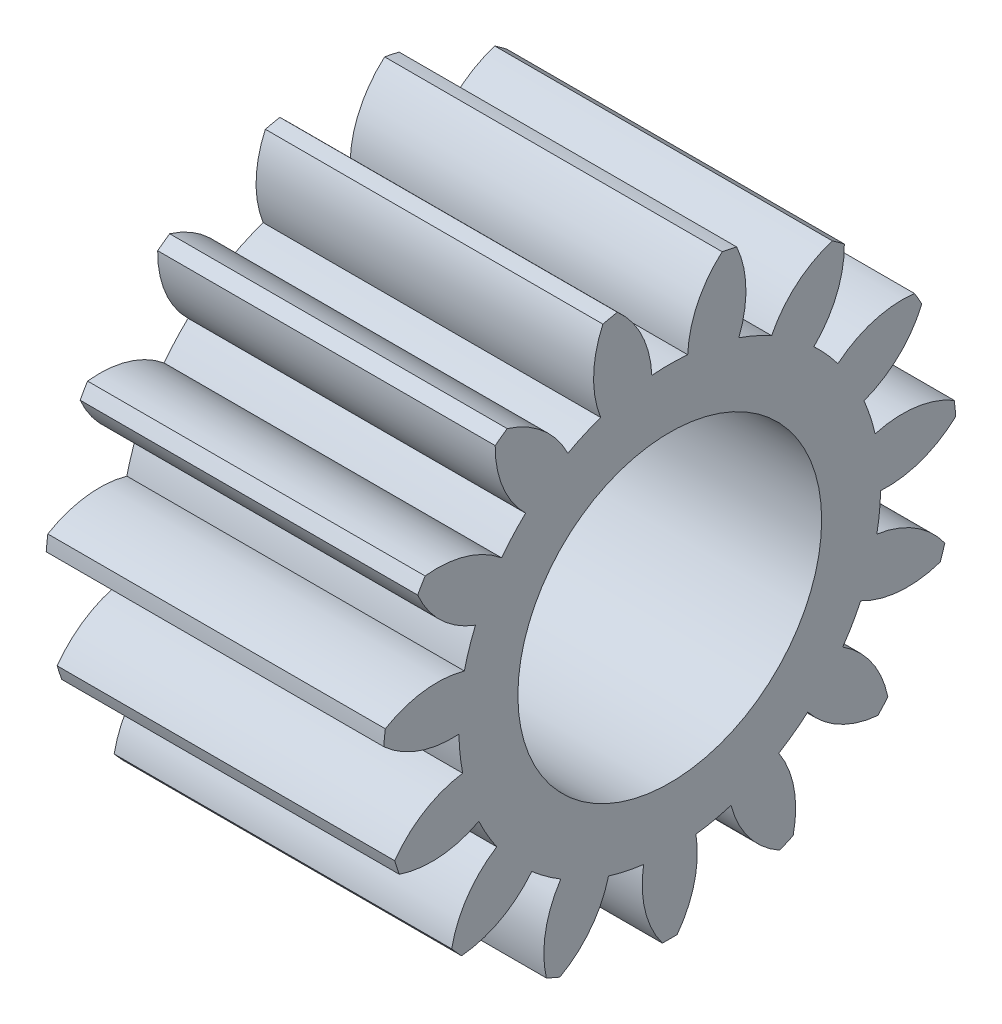
SolidWorks part; units mm, degrees
ref_plane "Plane1" through (0, 0, 0) normal (0, 0, 1) x (1, 0, 0)
ref_plane "Plane2" through (0, 0, 0) normal (0, 1, 0) x (1, 0, 0)
ref_plane "Plane3" through (0, 0, 0) normal (1, 0, 0) x (0, 0, -1)
other "Configuration Table"
sketch "HoldingSke" plane through (0, 0, 0) normal (0, 1, 0) x (1, 0, 0)
  line L0 (0, 0) -> (1.9319, -0.5176)
  line L1 (-15, 0) -> (100, 0) construction
  line L2 (0, 0) -> (-2.1039, 2.3779)
  line L3 (0, 0) -> (-11.863, 4.5341)
  line L4 (0, 0) -> (8.3417, 2.2352)
  line L5 (0, 0) -> (-46.8476, -17.4728)
  line L6 (0, 0) -> (-4.1448, -2.7965)
  line L7 (-2.1039, 2.3779) -> (8.6586, 51.2061)
  line L8 (-76.2, 54.61) -> (-75.7, 54.61)
  line L9 (-71.009, 38.7566) -> (-53.1078, 45.2721)
  line L10 (-76.2, 71.12) -> (104.1128, 71.12)
  line L11 (0, 0) -> (-5, 0)
  line L12 (-76.2, 101.6) -> (-76.181, 101.6)
  line L13 (24.9733, 27.94) -> (52.9518, 28.4284)
  line L14 (24.9733, 27.94) -> (24.9743, 27.94)
  line L15 (24.9733, 27.94) -> (100.4006, 29.5858)
  line L16 (-63.627, -0.5) -> (-12.827, -0.5)
  circle A0 centre (0, 0) radius 1.5
  circle A1 centre (0, 0) radius 3.124
  circle A2 centre (0, 0) radius 37.5
  circle A3 centre (0, 0) radius 2.25
  dimension "MHD" = 6.248
  dimension "Hub_dia" = 75
  dimension "Bore" = 3
  dimension "MBD" = 4.5
  dimension "Num_teeth" = 15
  dimension "Pitch" = 2
  dimension "Overall_len" = 50
  dimension "Show_teeth" = 15
  dimension "Thickness" = 5
  dimension "OAL" = 50.0003
  dimension "T_dim" = 0.5
  dimension "Ap" = 20
  dimension "H" = 19.05
  dimension "Pitch_radius" = 180.3128
  dimension "Width" = 5
  dimension "Backlash" = 0.019
  dimension "Addendum_fac" = 1
  dimension "Dedendum_fac" = 1.25
  dimension "Clearance_fac" = 0.25
  dimension "Dedendum_add" = 0.001
  dimension "Module" = 0.5
sketch "BasProSke" plane through (0, 0, 0) normal (0, 1, 0) x (1, 0, 0)
  line L0 (-10, 0) -> (60, 0) construction
  line L1 (0, 0) -> (0, 4.25)
  line L2 (0, 0) -> (5, 0)
  line L3 (5, 0) -> (5, 4.25)
  line L4 (5, 4.25) -> (0, 4.25)
  dimension "Thickness" = 5
  dimension "Diameter" = 8.5
revolve "Base-Revolve" add sketch "BasProSke" angle 360 about L0
sketch "TooCutSke" plane through (0, 0, 0) normal (1, 0, 0) x (0, 0, -1)
  line L1 (0, 0) -> (0, 107) construction
  line L2 (0, 0) -> (-0.4252, 3.7258) construction
  line L3 (0, 0) -> (-1.5522, 7.3025) construction
  line L4 (-0.4252, 3.7258) -> (-0.7761, 3.6512) construction
  arc A0 (0.2658, 3.1127) -> (-0.2658, 3.1127) centre (0, 0) ccw
  arc A1 (0.8008, 4.1997) -> (-0.8008, 4.1997) centre (0, 0) ccw
  circle A2 centre (0, 0) radius 3.75 construction
  circle A3 centre (0, 0) radius 3.5238 construction
  arc A4 (-0.2658, 3.1127) -> (-0.8008, 4.1997) centre (-1.7645, 3.0503) ccw
  arc A5 (0.8008, 4.1997) -> (0.2658, 3.1127) centre (1.7645, 3.0503) ccw
  dimension "Root_dia" = 6.248
  dimension "Overcut_dia" = 8.5508
  dimension "Pitch_dia" = 7.5
  dimension "Base_dia" = 7.0477
  dimension "Flank_rad" = 1.5
  dimension "Half_ang" = 12
  dimension "Half_CT" = 0.3587
extrude "ToothCut" cut sketch "TooCutSke" along normal through all
fillet "Breaks" [suppressed] radius 0.01
fillet "RootFillets" [suppressed] radius 0.126
pattern_circular "TeethCuts" count 15 every 24 about axis through (-10, 0, 0) along (1, 0, 0) of "ToothCut", "RootFillets", "Breaks"
sketch "HubNeaOneSke" plane through (0, 0, 0) normal (-1, 0, 0) x (0, 0, 1)
  circle A0 centre (0, 0) radius 3.124
  dimension "Diameter" = 6.248
extrude "HubNearOne" [suppressed] add sketch "HubNeaOneSke" along normal blind 45.0003
sketch "HubNeaBotSke" plane through (0, 0, 0) normal (-1, 0, 0) x (0, 0, 1)
  circle A0 centre (0, 0) radius 3.124
  dimension "Diameter" = 6.248
extrude "HubNearBoth" [suppressed] add sketch "HubNeaBotSke" along normal blind 22.5002
ref_plane "FarPln" through (5, 0, 0) normal (1, 0, 0) x (0, 0, -1)
sketch "HubFarSke" plane through (5, 0, 0) normal (1, 0, 0) x (0, 0, -1)
  circle A0 centre (0, 0) radius 3.124
  dimension "Diameter" = 6.248
extrude "HubFar" [suppressed] add sketch "HubFarSke" along normal blind 22.5002
sketch "BorSke" plane through (0, 0, 0) normal (1, 0, 0) x (0, 0, -1)
  circle A0 centre (0, 0) radius 2.25
  dimension "Diameter" = 4.5
extrude "Bore" cut sketch "BorSke" along normal mid plane 100.0006
sketch "KeySke" plane through (0, 0, 0) normal (1, 0, 0) x (0, 0, -1)
  line L0 (-0.6, 0) -> (-0.6, 2.75)
  line L1 (-0.6, 2.75) -> (0.6, 2.75)
  line L2 (0.6, 2.75) -> (0.6, 0)
  line L3 (0, 0) -> (0, 34) construction
  line L4 (-0.6, 0) -> (0.6, 0)
  dimension "Offset" = 2.75
  dimension "Width" = 1.2
extrude "Keyway" [suppressed] cut sketch "KeySke" along normal mid plane 100.0006
pattern_circular "Keyway2" [suppressed] count 2 every 90 about axis through (-10, 0, 0) along (1, 0, 0)
equation "' \"Module@HoldingSke\" = 6.35"
equation "' \"Num_teeth@HoldingSke\" = 12"
equation "' \"Ap@HoldingSke\" =  20"
equation "' \"Ap@HoldingSke\" = 20"
equation "' \"Width@HoldingSke\" = 0.5 * 25.4"
equation "' \"Hub_dia@HoldingSke\"= 1 * 25.4"
equation "' \"Hub_dia@HoldingSke\" = 1 * 25.4"
equation "' \"Overall_len@HoldingSke\" = 1.0 * 25.4"
equation "' \"Bore@HoldingSke\" = 0.75 * 25.4"
equation "' \"T_dim@HoldingSke\" = 0.1 * 25.4"
equation "' \"Width@KeySke\" = 0.25 * 25.4"
equation "' \"Show_teeth@HoldingSke\" = 13"
equation "' \"Backlash@HoldingSke\" = 0.009 * 25.4"
equation "' \"Addendum_fac@HoldingSke\" = 1.0"
equation "' \"Dedendum_fac@HoldingSke\" = 1.25"
equation "' \"Dedendum_add@HoldingSke\" = 0.00005 * 25.4"
equation "' \"Clearance_fac@HoldingSke\" = 0.25"
equation "\"Pitch@HoldingSke\" = 1 / \"Module@HoldingSke\""
equation "\"Overcut_dia@TooCutSke\" = (\"Num_teeth@HoldingSke\" + 2 * \"Addendum_fac@HoldingSke\") / \"Pitch@HoldingSke\" + 0.002 * 25.4"
equation "\"Pitch_dia@TooCutSke\" = \"Num_teeth@HoldingSke\" / \"Pitch@HoldingSke\""
equation "\"Base_dia@TooCutSke\" = \"Num_teeth@HoldingSke\" / \"Pitch@HoldingSke\" * cos((\"Ap@HoldingSke\"  * 3.14159265 / 180))"
equation "\"Root_dia@TooCutSke\" = (\"Num_teeth@HoldingSke\" + 2) / \"Pitch@HoldingSke\" - 2 * (\"Addendum_fac@HoldingSke\" + \"Dedendum_fac@HoldingSke\") / \"Pitch@HoldingSke\" - \"Dedendum_add@HoldingSke\" * 2"
equation "\"Half_ang@TooCutSke\" = 180 / \"Num_teeth@HoldingSke\""
equation "\"Half_CT@TooCutSke\" = \"Num_teeth@HoldingSke\" / \"Pitch@HoldingSke\" * sin((3.14159265 / 2 / \"Num_teeth@HoldingSke\")) / 2 - 7 * \"Backlash@HoldingSke\" / 4"
equation "\"Flank_rad@TooCutSke\" = \"Num_teeth@HoldingSke\" / \"Pitch@HoldingSke\" / 5"
equation "\"Radius@RootFillets\" = \"Clearance_fac@HoldingSke\" / \"Pitch@HoldingSke\" + \"Dedendum_add@HoldingSke\""
equation "\"Break_rad@Breaks\" = 0.02 / \"Pitch@HoldingSke\""
equation "\"Thickness@HoldingSke\" = \"Width@HoldingSke\""
equation "\"OAL@HoldingSke\" = \"Thickness@HoldingSke\""
equation "\"MHD@HoldingSke\" = (\"Num_teeth@HoldingSke\" + 2) / \"Pitch@HoldingSke\" - 2 * (\"Addendum_fac@HoldingSke\" + \"Dedendum_fac@HoldingSke\")  / \"Pitch@HoldingSke\" - \"Dedendum_add@HoldingSke\" * 2"
equation "\"MBD@HoldingSke\" = (\"Num_teeth@HoldingSke\" + 2) / \"Pitch@HoldingSke\" - 2 * (\"Addendum_fac@HoldingSke\" + \"Dedendum_fac@HoldingSke\")  / \"Pitch@HoldingSke\" - \"Dedendum_add@HoldingSke\" * 2 - 0.002 * 25.4"
equation "\"MHD@HoldingSke\" = ((sgn( \"MHD@HoldingSke\" - \"Hub_dia@HoldingSke\" )-1)*( \"MHD@HoldingSke\" - \"Hub_dia@HoldingSke\" ))/-2+ \"Hub_dia@HoldingSke\""
equation "\"OAL@HoldingSke\" = ((sgn( \"OAL@HoldingSke\" - \"Overall_len@HoldingSke\" )+1)*( \"OAL@HoldingSke\" - \"Overall_len@HoldingSke\" ))/2 + \"Overall_len@HoldingSke\" + 0.000002 * 25.4"
equation "\"Num_teeth@TeethCuts\" = int( \"Show_teeth@HoldingSke\" ) + 1"
equation "\"Num_teeth@TeethCuts\" = ((sgn( \"Num_teeth@TeethCuts\" - \"Num_teeth@HoldingSke\" )-1)*( \"Num_teeth@TeethCuts\" - \"Num_teeth@HoldingSke\" ))/-2+ \"Num_teeth@HoldingSke\""
equation "\"Num_teeth@TeethCuts\" = ((sgn( \"Num_teeth@TeethCuts\" - 2.0)+1)*( \"Num_teeth@TeethCuts\" - 2.0))/2 +2.0"
equation "\"Angle@TeethCuts\" = 360.0 / \"Num_teeth@HoldingSke\""
equation "\"Diameter@BasProSke\" = (\"Num_teeth@HoldingSke\" + 2 * \"Addendum_fac@HoldingSke\") / \"Pitch@HoldingSke\""
equation "\"Thickness@BasProSke\"  = \"Thickness@HoldingSke\""
equation "' \"Fillet_rad@BasProSke\" =  \"Thickness@HoldingSke\" * 0.05"
equation "' \"Fillet_rad@BasProSke\" = \"Thickness@HoldingSke\" * 0.05"
equation "\"MHD@HoldingSke\" = ((sgn( \"MHD@HoldingSke\" - \"Root_dia@TooCutSke\" )-1)*( \"MHD@HoldingSke\" - \"Root_dia@TooCutSke\" ))/-2+ \"Root_dia@TooCutSke\""
equation "\"Diameter@HubNeaOneSke\" = \"MHD@HoldingSke\""
equation "\"Length@HubNearOne\" = \"OAL@HoldingSke\" - \"Thickness@BasProSke\""
equation "\"Diameter@HubNeaBotSke\" = \"MHD@HoldingSke\""
equation "\"Length@HubNearBoth\" = ( \"OAL@HoldingSke\" - \"Thickness@BasProSke\" ) / 2.0"
equation "\"Thickness@FarPln\" = \"Thickness@BasProSke\""
equation "\"Diameter@HubFarSke\" = \"MHD@HoldingSke\""
equation "\"Length@HubFar\" = ( \"OAL@HoldingSke\" - \"Thickness@BasProSke\" ) / 2.0"
equation "\"Diameter@BorSke\" = \"MBD@HoldingSke\""
equation "\"D1@Bore\" = \"OAL@HoldingSke\" * 2.0"
equation "\"D1@Keyway\" = \"OAL@HoldingSke\" * 2.0"
equation "\"Offset@KeySke\" = \"T_dim@HoldingSke\" + \"MBD@HoldingSke\" / 2.0"
